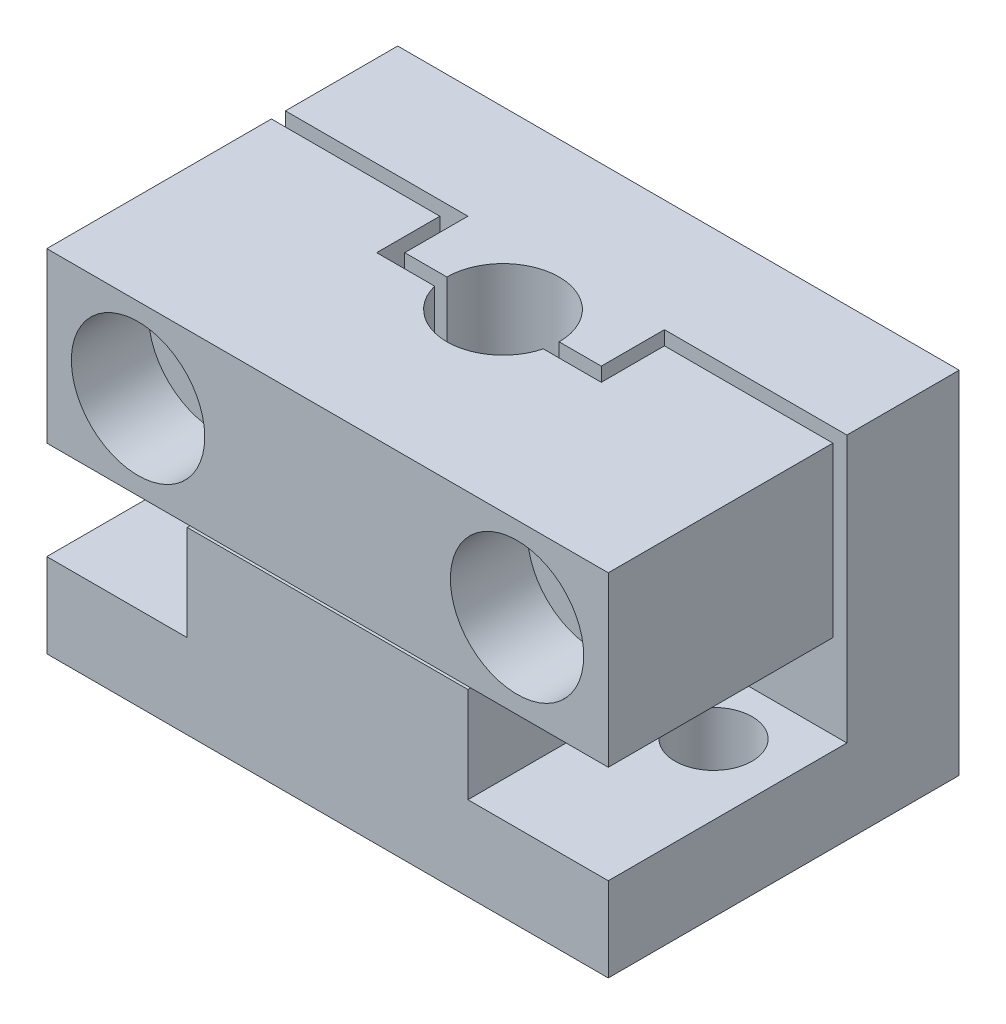
SolidWorks part; units mm, degrees
ref_plane "前视基准面" through (0, 0, 0) normal (0, 0, 1) x (1, 0, 0)
ref_plane "上视基准面" through (0, 0, 0) normal (0, 1, 0) x (1, 0, 0)
ref_plane "右视基准面" through (0, 0, 0) normal (1, 0, 0) x (0, 0, -1)
sketch "草图2" plane through (0, 0, 0) normal (1, 0, 0) x (0, 0, -1)
  line L0 (0, 0) -> (0, 45.6508) construction
  line L1 (-12.5, 25) -> (12.5, 25)
  line L2 (-12.5, 25) -> (-12.5, 0)
  line L3 (-12.5, 0) -> (12.5, 0)
  line L4 (12.5, 25) -> (12.5, 0)
  line L5 (0, 0) -> (51.1573, 0) construction
  dimension "D1" = 25
  dimension "D2" = 25
extrude "凸台-拉伸2" add sketch "草图2" along normal mid plane 40
sketch "草图8" plane through (20, 0, 0) normal (1, 0, 0) x (0, 0, -1)
  line L0 (-12.5, 25) -> (-12.5, 0) construction
  line L1 (-12.5, 6) -> (4.5, 6)
  line L2 (-12.5, 6) -> (-12.5, 13)
  line L3 (-12.5, 13) -> (4.5, 13)
  line L4 (4.5, 6) -> (4.5, 13)
  line L5 (12.5, 25) -> (-12.5, 25) construction
  line L6 (12.5, 0) -> (12.5, 25) construction
  line L7 (-12.5, 0) -> (12.5, 0) construction
  dimension "D1" = 12
  dimension "D2" = 8
  dimension "D3" = 6
extrude "切除-拉伸5" cut sketch "草图8" against normal blind 10
mirror "镜向1" about plane through (0, 0, 0) normal (1, 0, 0) of "切除-拉伸5"
sketch "草图12" plane through (0, 25, 0) normal (0, 1, 0) x (1, 0, 0)
  line L0 (-20, 4.5) -> (-7, 4.5)
  line L1 (-20, 12.5) -> (-20, -12.5) construction
  line L2 (-7, 4.5) -> (-7, 0)
  line L3 (-7, 0) -> (7, 0)
  line L4 (7, 0) -> (7, 4.5)
  line L5 (7, 4.5) -> (20, 4.5)
  line L6 (20, 12.5) -> (20, -12.5) construction
  line L8 (-10, 4.5) -> (-20, 4.5) construction
  line L9 (10, 4.5) -> (20, 4.5) construction
  line L10 (-20, 4.5) -> (-20, 3.5)
  line L11 (-20, 3.5) -> (-8, 3.5)
  line L12 (-8, 3.5) -> (-8, -1)
  line L13 (-8, -1) -> (8, -1)
  line L14 (8, -1) -> (8, 3.5)
  line L15 (8, 3.5) -> (20, 3.5)
  line L16 (20, 3.5) -> (20, 4.5)
  dimension "D1" = 14
  dimension "D2" = 1
  dimension "D3" = 1
  dimension "D4" = 1
  dimension "D5" = 1
  dimension "D6" = 1
extrude "切除-拉伸6" cut sketch "草图12" against normal up to surface (12 mm away) up to face at (-15, 13, 4)
sketch "草图13" plane through (0, 0, 12.5) normal (0, 0, 1) x (1, 0, 0)
  line L0 (10, 13) -> (10, 6) construction
  line L1 (-10, 13) -> (10, 13)
  line L2 (-10, 13) -> (-10, 12.8)
  line L3 (-10, 12.8) -> (10, 12.8)
  line L4 (10, 13) -> (10, 12.8)
  dimension "D1" = 0.2
extrude "切除-拉伸7" cut sketch "草图13" against normal up to surface (12.5 mm away) up to face at (0, 19, 0)
hole_wizard "孔1" positions "草图10" profile "草图9" legacy
sketch "草图10" plane through (0, 0, 12.5) normal (0, 0, 1) x (1, 0, 0)
  line L0 (0, 0) -> (0, 28.295) construction
  line L1 (20, 0) -> (-20, 0) construction
  line L3 (-20, 19) -> (-13.5, 19) construction
  line L4 (-20, 25) -> (-20, 13) construction
  point P0 (-13.5, 19)
  point P11 (13.5, 19)
  dimension "D1" = 27
sketch "草图9" plane through (-13.5, 19, 12.5) normal (1, 0, 0) x (0, -1, 0)
  line L0 (0, 0) -> (0, 16)
  line L1 (0, 16) -> (2.75, 16)
  line L2 (2.75, 16) -> (2.75, 5.5)
  line L3 (2.75, 5.5) -> (4.75, 5.5)
  line L4 (4.75, 5.5) -> (4.75, 0)
  line L5 (4.75, 0) -> (0, 0)
  line L6 (0, 110) -> (0, -10) construction
  dimension "直径" = 5.5
  dimension "深度" = 16
  dimension "柱坑直径" = 9.5
  dimension "柱坑深度" = 5.5
hole_wizard "M5x0.8 螺纹孔1" positions "草图15" profile "草图14" tap size "M5x0.8" standard "JIS"
sketch "草图15" plane through (0, 0, -4.5) normal (0, 0, 1) x (1, 0, 0)
  point P1 (-13.5, 19)
  point P4 (13.5, 19)
sketch "草图14" plane through (-13.5, 19, -4.5) normal (1, 0, 0) x (0, -1, 0)
  line L0 (0, 0) -> (0, 13.6618)
  line L1 (0, 13.6618) -> (2.1, 12.4)
  line L2 (2.1, 12.4) -> (2.1, 0)
  line L5 (2.1, 0) -> (0, 0)
  line L10 (0, 13.6618) -> (-2.1, 12.4) construction
  line L11 (0, -6.35) -> (0, 107.95) construction
  dimension "螺纹孔钻头直径" = 4.2
  dimension "螺纹孔钻头深度" = 12.4
  dimension "导头角度" = 118
cosmetic thread "孔螺蚊线1" parameters "D1"=8, "D2"=5
cosmetic thread "孔螺蚊线2" parameters "D1"=8, "D2"=5
sketch "草图16" plane through (0, 25, 0) normal (0, 1, 0) x (1, 0, 0)
  circle A0 centre (0, 0) radius 4
  dimension "D1" = 8
extrude "切除-拉伸8" cut sketch "草图16" against normal through all
sketch "草图17" plane through (0, 0, 0) normal (0, -1, 0) x (1, 0, 0)
  line L0 (0, 0) -> (0, 9.3526) construction
  line L1 (0, 0) -> (15, 0) construction
  circle A0 centre (-15, 0) radius 2.75
  circle A1 centre (15, 0) radius 2.75
  dimension "D2" = 5.5
  dimension "D1" = 30
extrude "切除-拉伸9" cut sketch "草图17" against normal up to surface (6 mm away) up to face at (-15, 6, 4)
